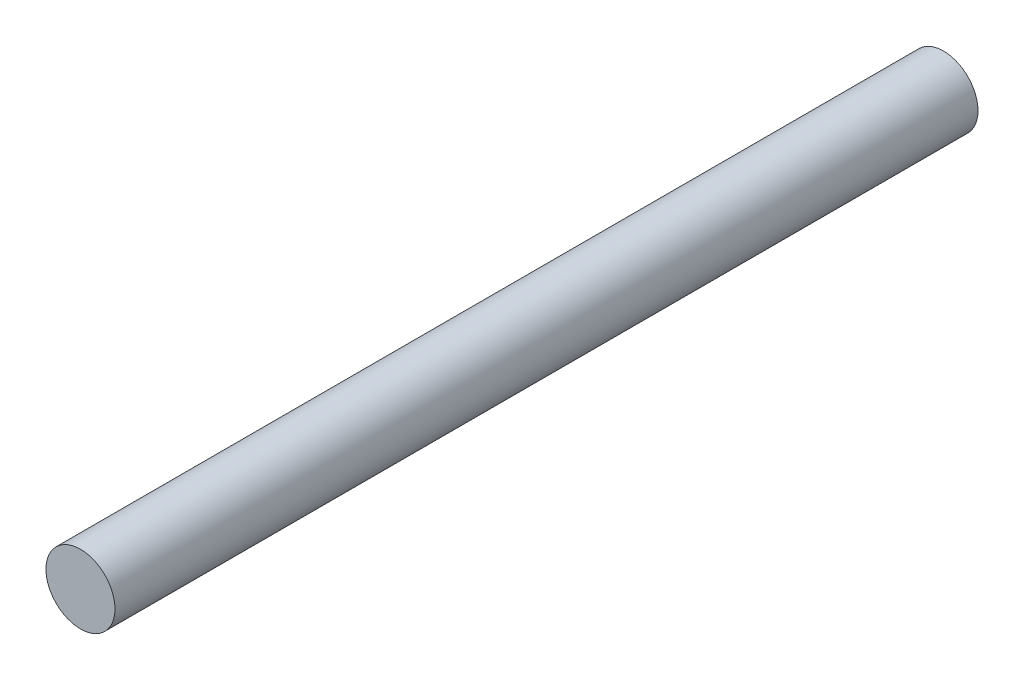
SolidWorks part; units mm, degrees
ref_plane "Plan de face" through (0, 0, 0) normal (1, 0, 0) x (0, 1, 0)
ref_plane "Plan de dessus" through (0, 0, 0) normal (0, 0, 1) x (0, 1, 0)
ref_plane "Plan de droite" through (0, 0, 0) normal (0, 1, 0) x (-1, 0, 0)
sketch "Esquisse1" plane through (0, 0, 0) normal (0, 0, 1) x (0, 1, 0)
  circle A0 centre (0, 0) radius 4
  dimension "D1" = 8
extrude "Boss.-Extru.1" add sketch "Esquisse1" along normal blind 100
